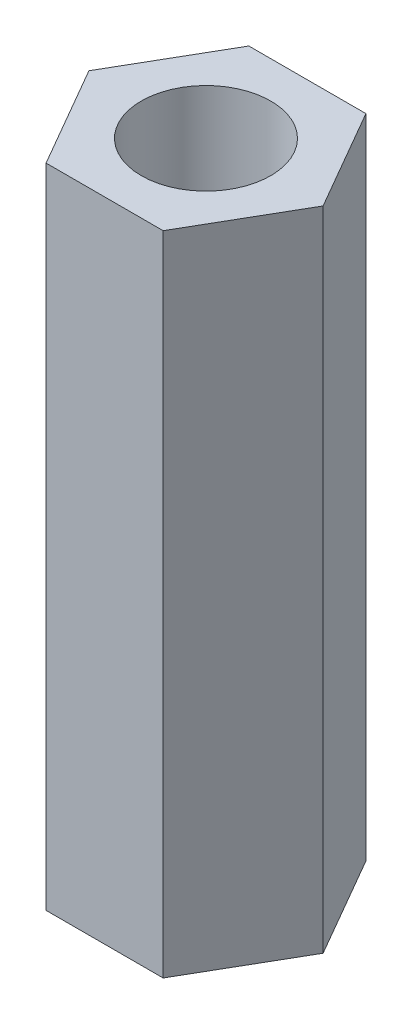
SolidWorks part; units mm, degrees
material "黄铜"
ref_plane "前视基准面" through (0, 0, 0) normal (0, 0, 1) x (1, 0, 0)
ref_plane "上视基准面" through (0, 0, 0) normal (0, 1, 0) x (1, 0, 0)
ref_plane "右视基准面" through (0, 0, 0) normal (1, 0, 0) x (0, 0, -1)
sketch "草图1" plane through (0, 0, 0) normal (0, 1, 0) x (1, 0, 0)
  line L1 (2.7135, 0) -> (1.3568, 2.35)
  line L2 (1.3568, 2.35) -> (-1.3568, 2.35)
  line L3 (-1.3568, 2.35) -> (-2.7135, 0)
  line L4 (-2.7135, 0) -> (-1.3568, -2.35)
  line L5 (-1.3568, -2.35) -> (1.3568, -2.35)
  line L6 (1.3568, -2.35) -> (2.7135, 0)
  circle A0 centre (0, 0) radius 2.35 construction
  circle A1 centre (0, 0) radius 1.5
  dimension "D2" = 3
  dimension "D1" = 4.7
extrude "凸台-拉伸2" add sketch "草图1" along normal blind 15
